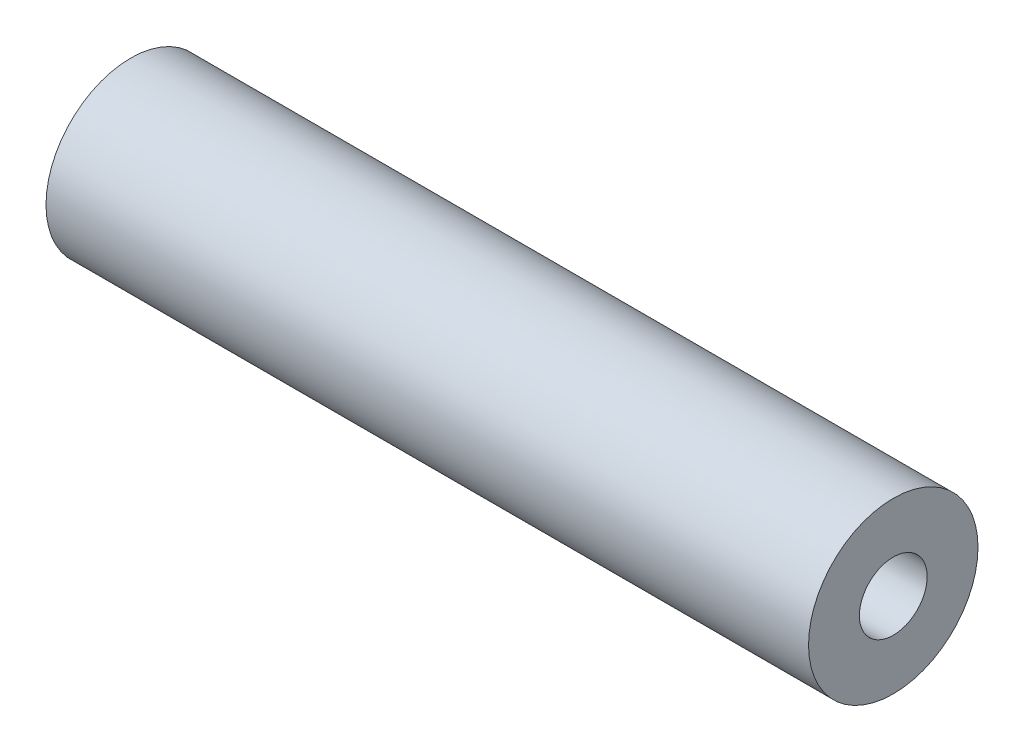
SolidWorks part; units mm, degrees
material "ﾎﾟﾘｵｷｼﾒﾁﾚﾝ(POM)ｱｾﾀｰﾙ共重合体"
ref_plane "正面" through (0, 0, 0) normal (0, 0, 1) x (1, 0, 0)
ref_plane "平面" through (0, 0, 0) normal (0, 1, 0) x (1, 0, 0)
ref_plane "右側面" through (0, 0, 0) normal (1, 0, 0) x (0, 0, -1)
sketch "ｽｹｯﾁ1" plane through (0, 0, 0) normal (0, 0, 1) x (1, 0, 0)
  line L0 (0, 0) -> (50000, 0) construction
  line L1 (-45, 10) -> (45, 10)
  line L2 (-45, 10) -> (-45, 4)
  line L3 (-45, 4) -> (45, 4)
  line L4 (45, 10) -> (45, 4)
  point P4 (0, 10)
  dimension "D1" = 90
  dimension "D2" = 8
  dimension "D3" = 20
revolve "回転1" add sketch "ｽｹｯﾁ1" angle 360 about L0
